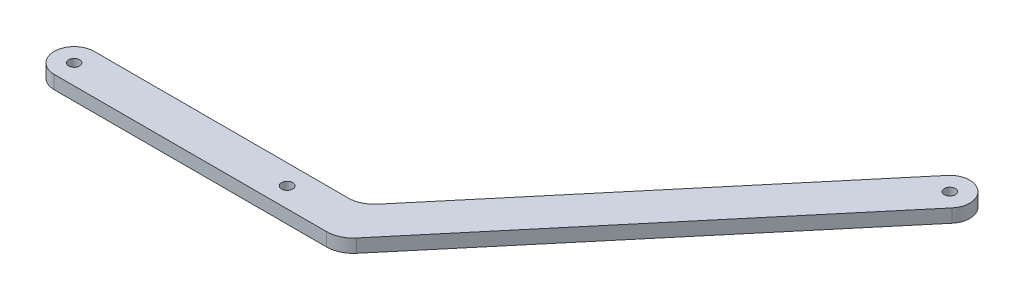
SolidWorks part; units mm, degrees
ref_plane "Front Plane" through (0, 0, 0) normal (0, 0, 1) x (1, 0, 0)
ref_plane "Top Plane" through (0, 0, 0) normal (0, 1, 0) x (1, 0, 0)
ref_plane "Right Plane" through (0, 0, 0) normal (1, 0, 0) x (0, 0, -1)
sketch "Sketch2" plane through (0, 0, 0) normal (0, 1, 0) x (1, 0, 0)
  line L0 (68.1093, 14.2756) -> (192.0616, 161.9963)
  line L1 (-62.6973, 9.739) -> (58.3806, 9.739)
  line L3 (-62.6973, -9.311) -> (64.3027, -9.311)
  line L5 (206.6548, 149.7512) -> (76.9925, -4.7744)
  line L6 (64.3027, -9.311) -> (67.2637, -9.311)
  line L7 (-62.6973, 0.214) -> (111.9385, 0.214) construction
  arc A0 (192.0616, 161.9963) -> (206.6548, 149.7512) centre (199.3582, 155.8737) cw
  arc A1 (67.2637, -9.311) -> (76.9925, -4.7744) centre (67.2637, 3.389) ccw
  arc A2 (58.3806, 9.739) -> (68.1093, 14.2756) centre (58.3806, 22.439) ccw
  arc A3 (-62.6973, 9.739) -> (-62.6973, -9.311) centre (-62.6973, 0.214) ccw
  circle A4 centre (-62.6973, 0.214) radius 2.6035
  circle A5 centre (199.3582, 155.8737) radius 2.6035
  circle A6 centre (38.9027, 0.214) radius 2.667
  dimension "D5" = 9.525
  dimension "D6" = 12.7
  dimension "D4" = 12.7
  dimension "D7" = 9.525
  dimension "D8" = 5.207
  dimension "D9" = 5.207
  dimension "D10" = 5.334
  dimension "D1" = 127
  dimension "D2" = 19.05
  dimension "D3" = 130
  dimension "D11" = 101.6
  dimension "D12" = 304.8
extrude "Boss-Extrude1" add sketch "Sketch2" along normal blind 6.35
